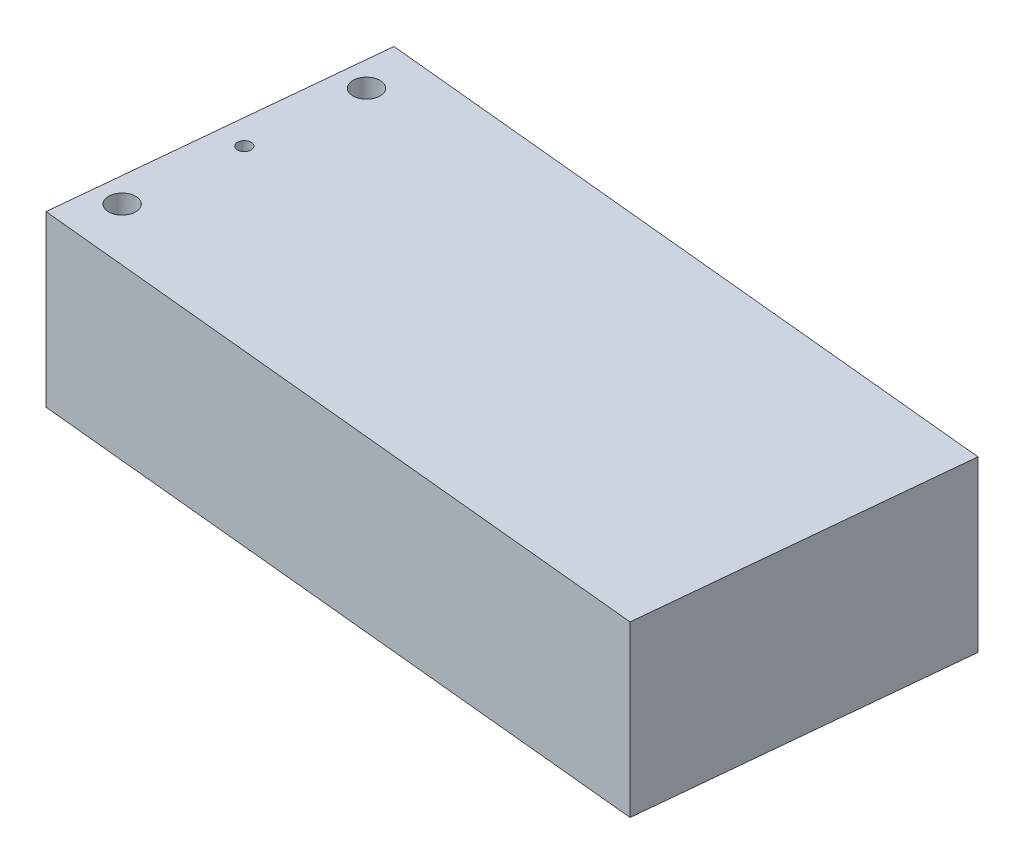
SolidWorks part; units mm, degrees
ref_plane "Спереди" through (0, 0, 0) normal (0, 0, 1) x (1, 0, 0)
ref_plane "Сверху" through (0, 0, 0) normal (0, 1, 0) x (1, 0, 0)
ref_plane "Справа" through (0, 0, 0) normal (1, 0, 0) x (0, 0, -1)
sketch "Эскиз1" plane through (0, 0, 0) normal (0, 1, 0) x (1, 0, 0)
  line L0 (0, 0) -> (95.544, -9.346)
  line L1 (95.544, -9.346) -> (100.1196, 37.4307)
  line L2 (0, 0) -> (4.5756, 46.7767)
  line L3 (4.5756, 46.7767) -> (100.1196, 37.4307)
  line L4 (0, 0) -> (3.981, -0.3894) construction
  line L5 (3.981, -0.3894) -> (8.5566, 46.3873) construction
  line L6 (6.2688, 22.999) -> (4.6625, 6.5773) construction
  line L7 (4.6625, 6.5773) -> (7.8752, 39.4206) construction
  circle A0 centre (4.6625, 6.5773) radius 2
  circle A1 centre (7.8752, 39.4206) radius 2
  circle A2 centre (6.2688, 22.999) radius 1
  dimension "D1" = 96
  dimension "D2" = 47
extrude "Бобышка-Вытянуть1" add sketch "Эскиз1" along normal blind 25
